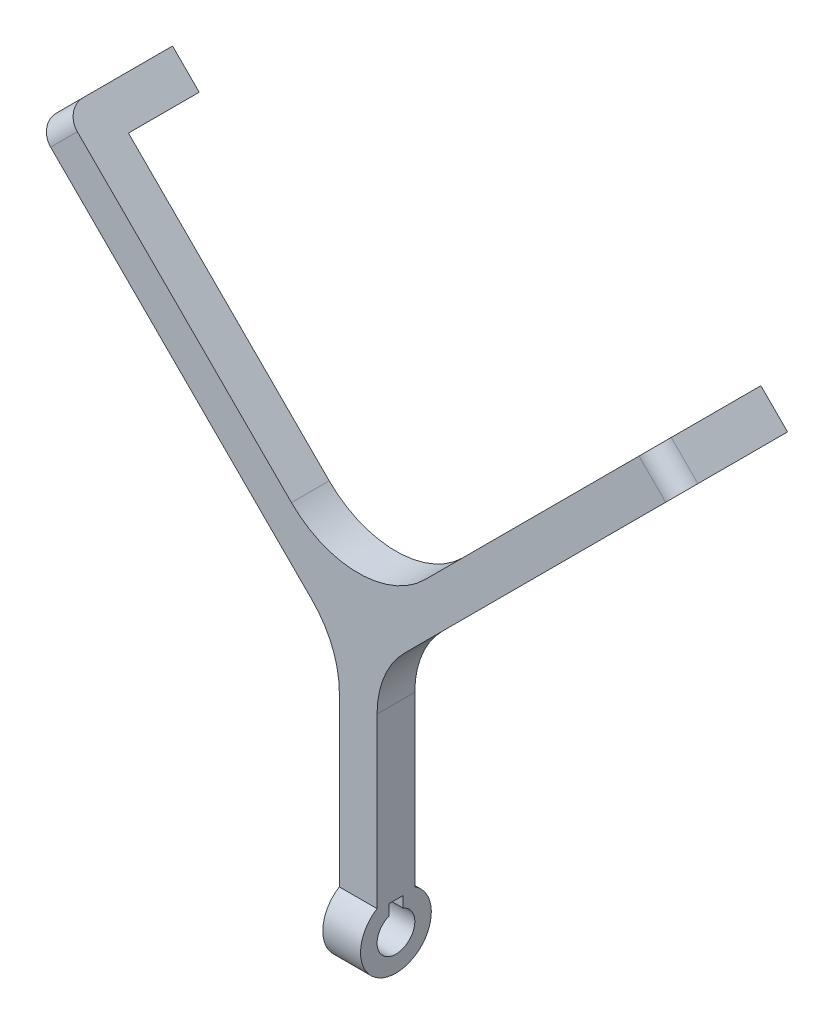
SolidWorks part; units mm, degrees
ref_plane "Plan de face" through (0, 0, 0) normal (0, 0, 1) x (1, 0, 0)
ref_plane "Plan de dessus" through (0, 0, 0) normal (0, 1, 0) x (1, 0, 0)
ref_plane "Plan de droite" through (0, 0, 0) normal (1, 0, 0) x (0, 0, -1)
sketch "Esquisse1" plane through (0, 0, 0) normal (0, 0, 1) x (1, 0, 0)
  line L1 (0, 0) -> (136, 0) construction
  line L2 (0, 0) -> (0, 120) construction
  line L3 (0, 120) -> (136, 120) construction
  line L4 (136, 0) -> (136, 120) construction
  line L16 (64, 0) -> (64, 50.3431)
  line L17 (64, 50.3431) -> (0, 114.3431)
  line L18 (0, 114.3431) -> (5.6569, 120)
  line L19 (5.6569, 120) -> (68, 57.6569)
  line L20 (68, 57.6569) -> (130.3431, 120)
  line L21 (130.3431, 120) -> (136, 114.3431)
  line L22 (136, 114.3431) -> (72, 50.3431)
  line L23 (72, 50.3431) -> (72, 0)
  line L24 (72, 0) -> (64, 0)
  point P19 (68, 0)
  dimension "D1" = 136
  dimension "D2" = 120
  dimension "D3" = 8
  dimension "D4" = 68
  dimension "D5" = 135
  dimension "D6" = 135
  dimension "D7" = 90
  dimension "D8" = 8
  dimension "D9" = 8
  dimension "D10" = 68
extrude "Boss.-Extru.1" add sketch "Esquisse1" along normal blind 8
sketch "Esquisse2" plane through (0, 0, 0) normal (0, 0, -1) x (-1, 0, 0)
  line L0 (-72, 50.3431) -> (-136, 114.3431) construction
  line L1 (-136, 114.3431) -> (-130.3431, 120) construction
  line L2 (-130.3431, 120) -> (-68, 57.6569) construction
  line L3 (-130.3431, 108.6863) -> (-136, 114.3431)
  line L4 (-136, 114.3431) -> (-130.3431, 120)
  line L5 (-130.3431, 120) -> (-124.6863, 114.3431)
  line L6 (-130.3431, 108.6863) -> (-124.6863, 114.3431)
  line L7 (0, 114.3431) -> (-64, 50.3431) construction
  line L8 (-68, 57.6569) -> (-5.6569, 120) construction
  line L9 (-5.6569, 120) -> (0, 114.3431) construction
  line L10 (0, 114.3431) -> (-5.6569, 108.6863)
  line L11 (-11.3137, 114.3431) -> (-5.6569, 120)
  line L12 (-5.6569, 120) -> (0, 114.3431)
  line L13 (-11.3137, 114.3431) -> (-5.6569, 108.6863)
  dimension "D1" = 8
  dimension "D2" = 8
extrude "Boss.-Extru.2" add sketch "Esquisse2" along normal blind 15
fillet "Congé1" radius 20 3 edges at (72, 50.3431, 4) (64, 50.3431, 4) (68, 57.6569, 4)
fillet "Congé2" radius 4 2 edges at (133.1716, 117.1716, 8) (2.8284, 117.1716, 8)
sketch "Esquisse3" plane through (64, 0, 0) normal (-1, 0, 0) x (0, 0, 1)
  line L0 (4, 0) -> (4, 33.6289) construction
  line L1 (8, 0) -> (0, 0) construction
  circle A0 centre (4, 0) radius 7.5
  dimension "D1" = 15
extrude "Boss.-Extru.3" add sketch "Esquisse3" against normal up to surface (8 mm away) up to face at (72, 21.0294, 4)
sketch "Esquisse4" plane through (64, 0, 0) normal (-1, 0, 0) x (0, 0, 1)
  line L5 (2.5, 3.7081) -> (2.5, 6)
  line L7 (4, 0) -> (4, 7.4852) construction
  line L9 (2.5, 6) -> (5.5, 6)
  line L10 (5.5, 3.7081) -> (5.5, 6)
  arc A0 (2.5, 3.7081) -> (5.5, 3.7081) centre (4, 0) ccw
  point P10 (4, 6)
  point P11 (4, 6)
  dimension "D1" = 8
  dimension "D2" = 3
  dimension "D3" = 6
extrude "Enlèv. mat.-Extru.1" cut sketch "Esquisse4" against normal through all
equation "\"long_tot\"= 120"
equation "\"espac_sub_arms\"= 120"
equation "\"épaiss_cadre\"= 8"
equation "\"long_protub\"= 15"
equation "\"rayon_conge\"= 3"
equation "\"diam_axe\"= 5"
equation "\"D1@Esquisse1\"=\"espac_sub_arms\"+\"épaiss_cadre\"*2"
equation "\"D2@Esquisse1\"=\"long_tot\""
equation "\"D3@Esquisse1\"=\"épaiss_cadre\""
equation "\"D4@Esquisse1\"=\"D1@Esquisse1\"/2"
equation "\"D6@Esquisse1\"=\"D5@Esquisse1\""
equation "\"D8@Esquisse1\"=\"épaiss_cadre\""
equation "\"D9@Esquisse1\"=\"épaiss_cadre\""
equation "\"D10@Esquisse1\"=\"D4@Esquisse1\""
equation "\"D1@Boss.-Extru.1\"=\"épaiss_cadre\""
equation "\"D1@Esquisse2\"=\"épaiss_cadre\""
equation "\"D2@Esquisse2\"=\"épaiss_cadre\""
equation "\"D1@Boss.-Extru.2\"=\"long_protub\""
